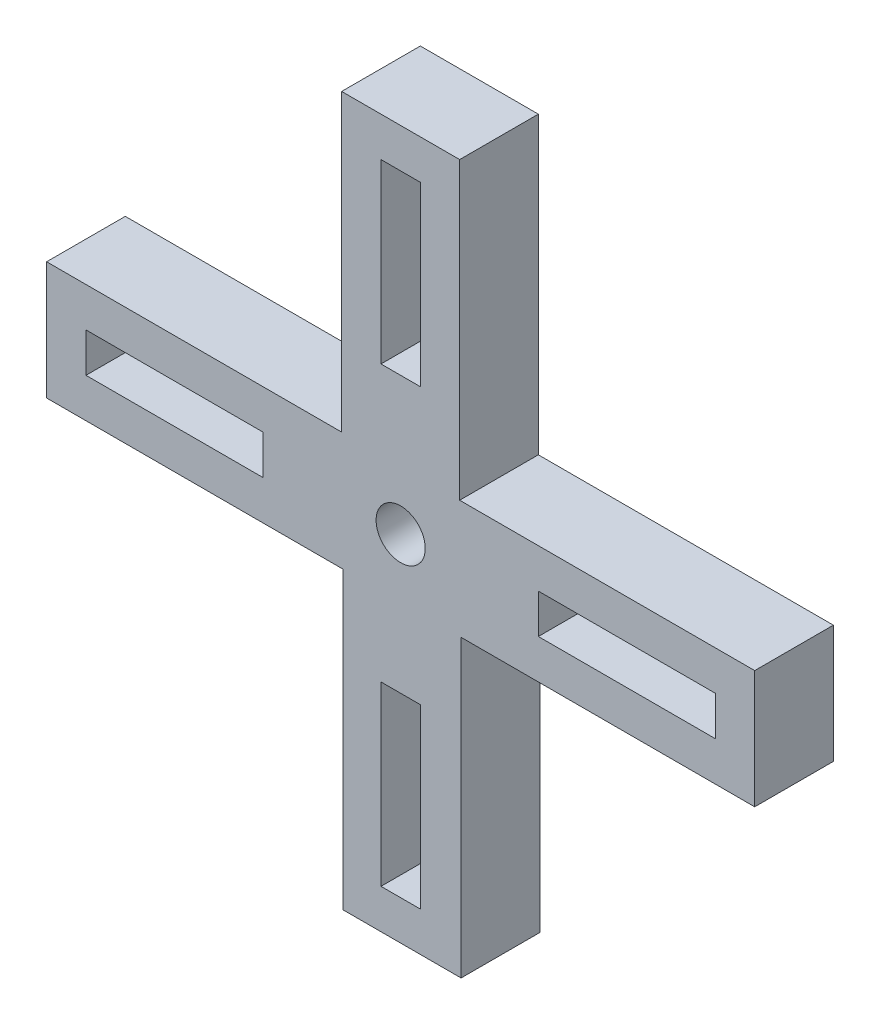
SolidWorks part; units mm, degrees
ref_plane "Plan de face" through (0, 0, 0) normal (0, 0, 1) x (1, 0, 0)
ref_plane "Plan de dessus" through (0, 0, 0) normal (0, 1, 0) x (1, 0, 0)
ref_plane "Plan de droite" through (0, 0, 0) normal (1, 0, 0) x (0, 0, -1)
sketch "Esquisse1" plane through (0, 0, 0) normal (0, 0, 1) x (1, 0, 0)
  line L0 (0, 0) -> (-6, 0)
  line L1 (-6, 0) -> (-6, -15)
  line L2 (-6, -15) -> (-21, -15)
  line L3 (-21, -15) -> (-21, -21)
  line L4 (-21, -21) -> (-5.9279, -21)
  line L5 (-5.9279, -21) -> (-5.9279, -36)
  line L6 (-5.9279, -36) -> (0.0721, -36)
  line L7 (0.0721, -36) -> (0.0721, -21)
  line L8 (0.0721, -21) -> (15, -21)
  line L9 (15, -21) -> (15, -15)
  line L10 (15, -15) -> (0, -15)
  line L11 (0, -15) -> (0, 0)
  line L12 (-2, -2) -> (-4, -2)
  line L13 (-4, -2) -> (-4, -11)
  line L14 (-4, -11) -> (-2, -11)
  line L15 (-2, -11) -> (-2, -2)
  line L16 (0, -15) -> (-6, -15)
  line L17 (-5.9279, -21) -> (-6, -15)
  line L18 (-5.9279, -21) -> (0.0721, -21)
  line L19 (0, -15) -> (0.0721, -21)
  line L20 (-19, -17) -> (-19, -19)
  line L21 (-19, -19) -> (-10, -19)
  line L22 (-10, -19) -> (-10, -17)
  line L23 (-10, -17) -> (-19, -17)
  line L25 (-4, -25) -> (-2, -25)
  line L26 (-4, -25) -> (-4, -34)
  line L27 (-4, -34) -> (-2, -34)
  line L28 (-2, -25) -> (-2, -34)
  line L29 (4, -17) -> (13, -17)
  line L30 (4, -17) -> (4, -19)
  line L31 (4, -19) -> (13, -19)
  line L32 (13, -17) -> (13, -19)
  line L33 (-21, -15) -> (-5.9279, -15)
  line L34 (-21, -15) -> (-21, -21)
  line L35 (-21, -21) -> (-5.9279, -21)
  line L36 (-5.9279, -15) -> (-5.9279, -21)
  line L37 (0, -15) -> (15, -15)
  line L38 (0, -15) -> (0, -21)
  line L39 (0, -21) -> (15, -21)
  line L40 (15, -15) -> (15, -21)
  line L41 (-5.9279, -21) -> (0.0721, -21)
  line L42 (-5.9279, -21) -> (-5.9279, -36)
  line L43 (-5.9279, -36) -> (0.0721, -36)
  line L44 (0.0721, -21) -> (0.0721, -36)
  line L45 (0, -15) -> (-6, -15)
  line L46 (0, -15) -> (0, 0)
  line L47 (0, 0) -> (-6, 0)
  line L48 (-6, -15) -> (-6, 0)
  dimension "D1" = 6
  dimension "D2" = 15
  dimension "D3" = 15
  dimension "D4" = 2
  dimension "D5" = 2
  dimension "D6" = 2
  dimension "D7" = 2
  dimension "D8" = 2
  dimension "D9" = 2
  dimension "D10" = 9
  dimension "D11" = 9
  dimension "D12" = 9
  dimension "D13" = 2
  dimension "D14" = 2
  dimension "D15" = 9
extrude "Boss.-Extru.4" add sketch "Esquisse1" along normal blind 4 contours L13 L14 L15 L12 | L11 L0 L1 L2 L3 L4 L5 L6 L7 L8 L9 L10 | L25 L28 L27 L26 | L29 L32 L31 L30 | L21 L22 L23 L20
sketch "Esquisse2" plane through (0, 0, 4) normal (0, 0, 1) x (1, 0, 0)
  line L0 (-21, -15) -> (-21, -21) construction
  line L1 (-5.9279, -36) -> (0.0721, -36) construction
  circle A0 centre (-3, -18) radius 1.25
  dimension "D3" = 2.5
  dimension "D1" = 18
  dimension "D2" = 18
extrude "Enlèv. mat.-Extru.1" cut sketch "Esquisse2" against normal blind 4
